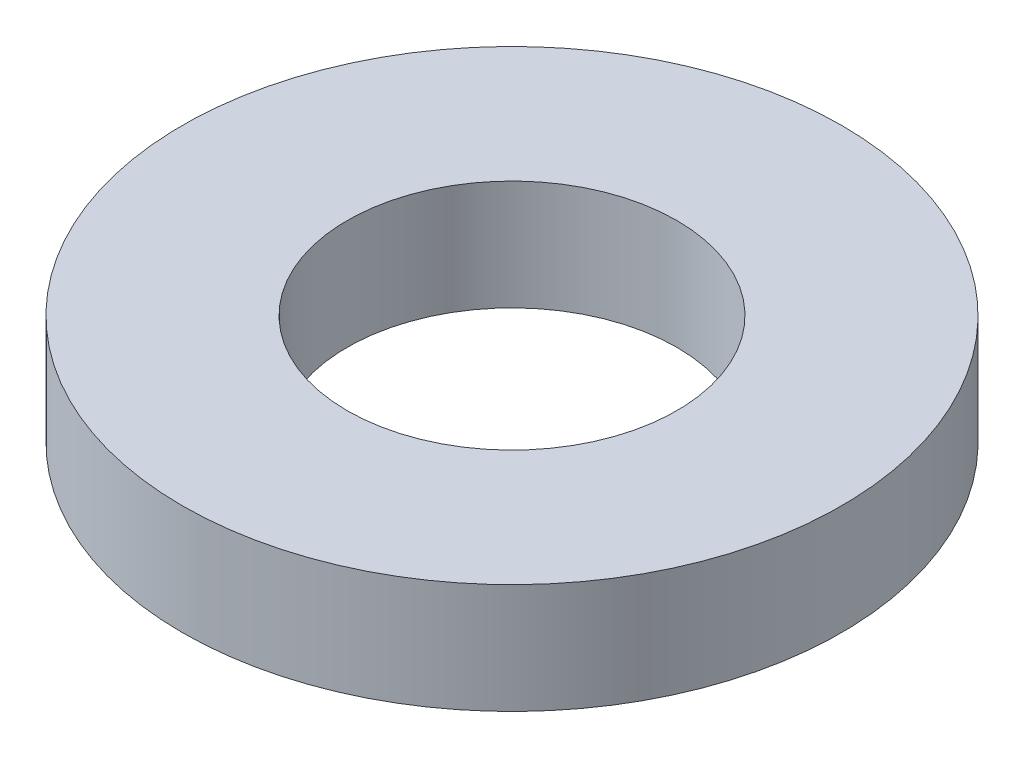
SolidWorks part; units mm, degrees
ref_plane "Спереди" through (0, 0, 0) normal (0, 0, 1) x (1, 0, 0)
ref_plane "Сверху" through (0, 0, 0) normal (0, 1, 0) x (1, 0, 0)
ref_plane "Справа" through (0, 0, 0) normal (1, 0, 0) x (0, 0, -1)
sketch "Эскиз1" plane through (0, 0, 0) normal (0, 1, 0) x (1, 0, 0)
  circle A0 centre (0, 0) radius 30
  circle A1 centre (0, 0) radius 15
  point P5 (0, 0)
  dimension "D1" = 60
  dimension "D2" = 30
extrude "Бобышка-Вытянуть1" add sketch "Эскиз1" along normal blind 10
